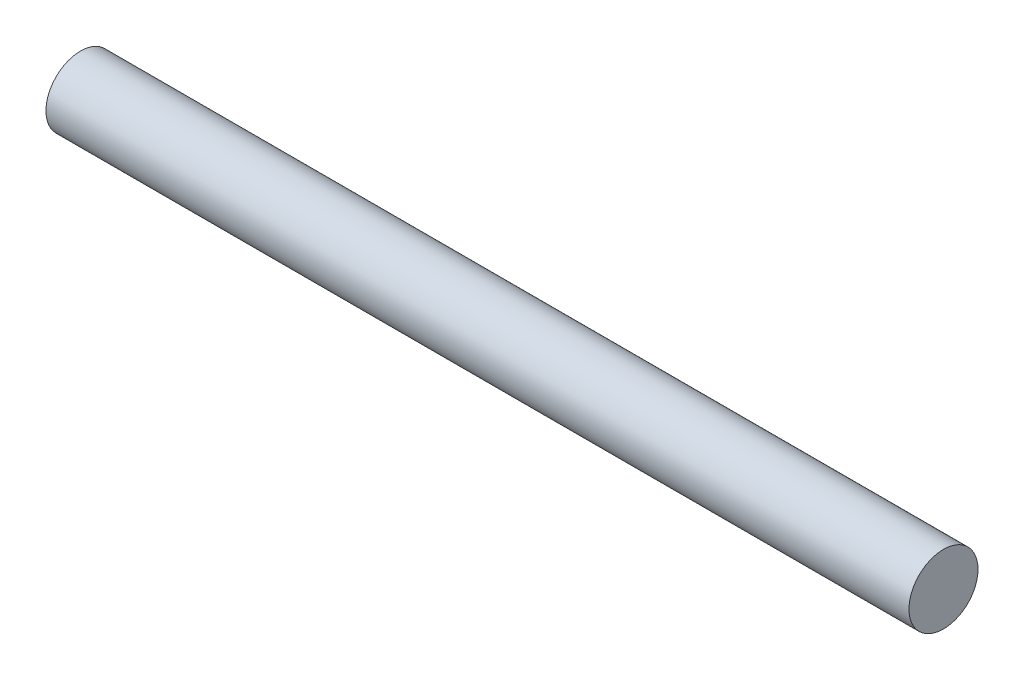
SolidWorks part; units mm, degrees
ref_plane "Ebene vorne" through (0, 0, 0) normal (0, 0, 1) x (1, 0, 0)
ref_plane "Ebene oben" through (0, 0, 0) normal (0, 1, 0) x (1, 0, 0)
ref_plane "Ebene rechts" through (0, 0, 0) normal (1, 0, 0) x (0, 0, -1)
sketch "Skizze1" plane through (0, 0, 0) normal (1, 0, 0) x (0, 0, -1)
  circle A0 centre (0, 0) radius 4
  dimension "D1" = 8
extrude "Aufsatz-Linear austragen1" add sketch "Skizze1" along normal blind 100
sketch "Skizze2" plane through (0, 0, 0) normal (-1, 0, 0) x (0, 0, 1)
  circle A0 centre (0, 0) radius 1.65
  dimension "D1" = 3.3
extrude "Schnitt-Linear austragen1" cut sketch "Skizze2" against normal blind 4
